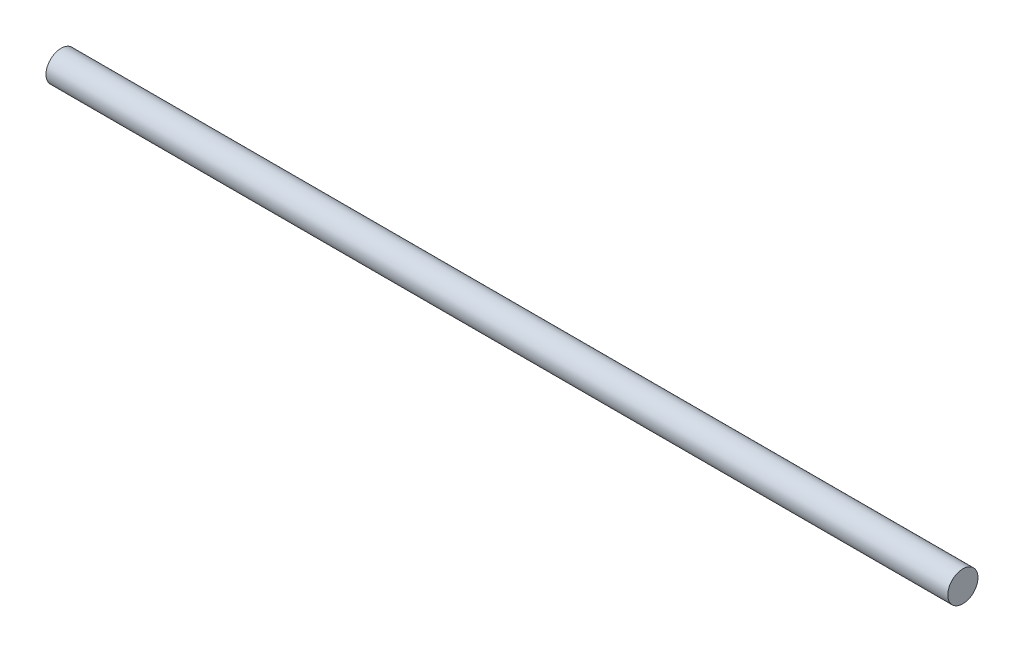
SolidWorks part; units mm, degrees
material "AISI 316 Stainless Steel Sheet (SS)"
ref_plane "Front Plane" through (0, 0, 0) normal (0, 0, 1) x (1, 0, 0)
ref_plane "Top Plane" through (0, 0, 0) normal (0, 1, 0) x (1, 0, 0)
ref_plane "Right Plane" through (0, 0, 0) normal (1, 0, 0) x (0, 0, -1)
sketch "Sketch1" plane through (0, 0, 0) normal (1, 0, 0) x (0, 0, -1)
  circle A0 centre (0, 0) radius 2.35
  dimension "D1" = 4.7
extrude "Boss-Extrude1" add sketch "Sketch1" along normal mid plane 140
